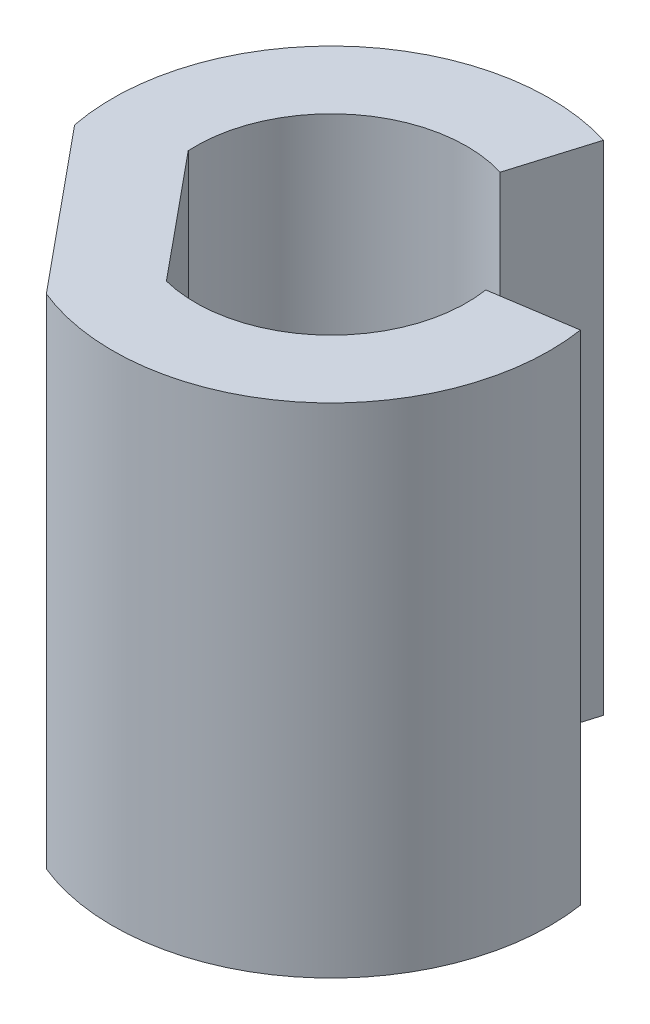
SolidWorks part; units mm, degrees
ref_plane "Front Plane" through (0, 0, 0) normal (0, 0, 1) x (1, 0, 0)
ref_plane "Top Plane" through (0, 0, 0) normal (0, 1, 0) x (1, 0, 0)
ref_plane "Right Plane" through (0, 0, 0) normal (1, 0, 0) x (0, 0, -1)
sketch "Sketch1" plane through (0, 0, 0) normal (0, 1, 0) x (1, 0, 0)
  line L6 (-0.6025, -2.3748) -> (-2.4462, -0.1363)
  line L7 (-1.488, -3.659) -> (-3.8763, -0.7594)
  line L8 (1.1424, 3.7812) -> (0.7086, 2.3453)
  line L9 (2.4216, 0.3722) -> (3.9041, 0.6001)
  arc A7 (-0.6025, -2.3748) -> (2.4216, 0.3722) centre (0, 0) ccw
  arc A8 (-2.4462, -0.1363) -> (0.7086, 2.3453) centre (0, 0) cw
  arc A9 (-1.488, -3.659) -> (3.9041, 0.6001) centre (0, 0) ccw
  arc A10 (-3.8763, -0.7594) -> (1.1424, 3.7812) centre (0, 0) cw
  dimension "D1" = 2.45
  dimension "D3" = 2.9
  dimension "D2" = 2.45
  dimension "D4" = 1.5
extrude "Boss-Extrude1" add sketch "Sketch1" along normal blind 9
